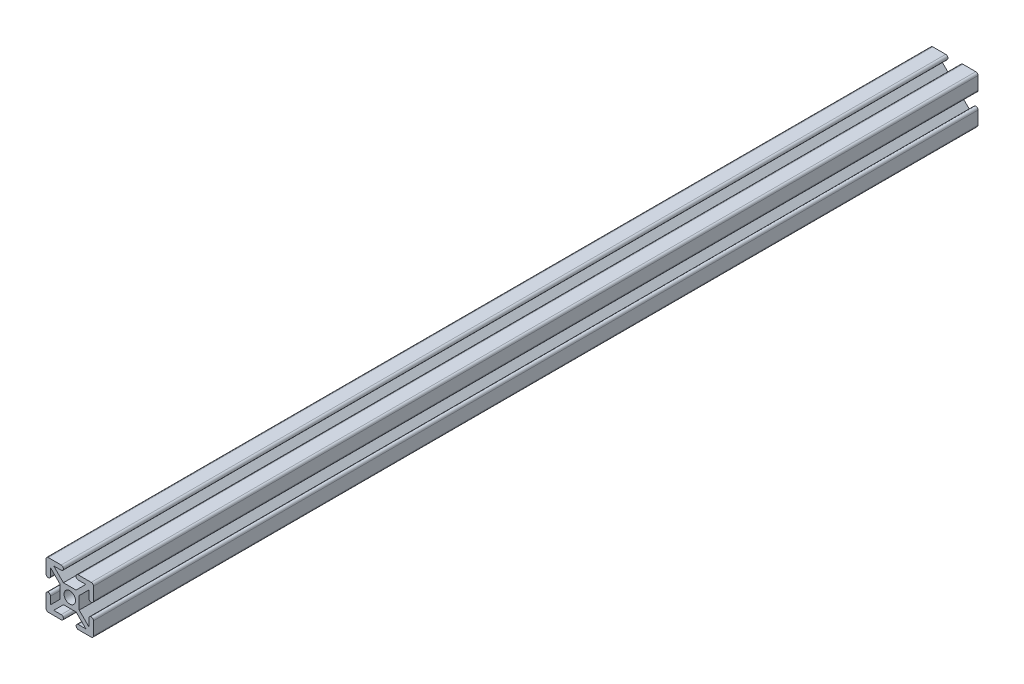
SolidWorks part; units mm, degrees
ref_plane "Alzado" through (0, 0, 0) normal (0, 0, 1) x (1, 0, 0)
ref_plane "Planta" through (0, 0, 0) normal (0, 1, 0) x (1, 0, 0)
ref_plane "Vista lateral" through (0, 0, 0) normal (1, 0, 0) x (0, 0, -1)
sketch "Croquis1" plane through (0, 0, 0) normal (0, 0, 1) x (1, 0, 0)
  line L0 (-21.181, 37.9272) -> (-21.181, 39.3522) construction
  line L1 (-2.1282, 21.7772) -> (2.5968, 21.7772)
  line L2 (-22.606, 47.5021) -> (-22.606, 39.3522)
  line L3 (-21.181, 48.9271) -> (-13.031, 48.9271)
  line L4 (-2.181, 48.9271) -> (5.969, 48.9271)
  line L5 (-17.7032, 21.7772) -> (-12.9782, 21.7772)
  line L6 (-13.606, 37.9272) -> (-13.606, 29.9272)
  line L7 (-22.5532, 28.5022) -> (-22.5532, 20.3522)
  line L8 (-21.1546, 18.9536) -> (-12.9782, 18.9272)
  line L9 (7.394, 47.5021) -> (7.394, 39.4559)
  line L10 (-19.756, 44.0772) -> (-19.756, 39.3522)
  line L11 (7.394, 28.6059) -> (7.394, 20.3522)
  line L12 (-11.606, 47.5021) -> (-13.031, 47.5021) construction
  line L13 (-2.1282, 18.9272) -> (5.969, 18.9272)
  line L14 (-17.756, 46.0771) -> (-13.031, 46.0771)
  line L15 (-19.756, 28.5022) -> (-19.756, 23.7772)
  line L16 (-3.606, 47.5021) -> (-2.181, 47.5021) construction
  line L17 (-2.181, 46.0771) -> (2.544, 46.0771)
  line L18 (5.969, 38.0309) -> (5.969, 39.4559) construction
  line L19 (-11.606, 39.9271) -> (-17.756, 46.0771)
  line L20 (4.544, 44.0771) -> (4.544, 39.4559)
  line L21 (5.969, 30.0309) -> (5.969, 28.6059) construction
  line L22 (-13.606, 37.9272) -> (-19.756, 44.0772)
  line L23 (4.544, 28.6059) -> (4.544, 23.7771)
  line L24 (-3.5532, 20.3522) -> (-2.1282, 20.3522) construction
  line L25 (-13.606, 29.9272) -> (-19.756, 23.7772)
  line L26 (-11.606, 39.9271) -> (-3.606, 39.9271)
  line L27 (-3.606, 39.9271) -> (2.544, 46.0771)
  line L28 (-21.1546, 29.9272) -> (-21.1546, 28.5022) construction
  line L29 (-17.7032, 21.7772) -> (-11.5532, 27.9272)
  line L30 (-11.5532, 27.9272) -> (-3.5532, 27.9272)
  line L31 (-3.5532, 27.9272) -> (2.5968, 21.7772)
  line L32 (-11.5532, 20.3522) -> (-12.9782, 20.3522) construction
  line L33 (-1.606, 29.9271) -> (4.544, 23.7771)
  line L34 (-1.606, 37.9271) -> (4.544, 44.0771)
  line L35 (-1.606, 37.9271) -> (-1.606, 29.9271)
  circle A0 centre (-7.5532, 33.9272) radius 3.645
  arc A1 (-22.606, 39.3522) -> (-19.756, 39.3522) centre (-21.181, 39.3522) ccw
  arc A2 (-13.031, 46.0771) -> (-13.031, 48.9271) centre (-13.031, 47.5021) ccw
  arc A3 (-2.181, 48.9271) -> (-2.181, 46.0771) centre (-2.181, 47.5021) ccw
  arc A4 (4.544, 39.4559) -> (7.394, 39.4559) centre (5.969, 39.4559) ccw
  arc A5 (7.394, 28.6059) -> (4.544, 28.6059) centre (5.969, 28.6059) ccw
  arc A6 (-2.1282, 21.7772) -> (-2.1282, 18.9272) centre (-2.1282, 20.3522) ccw
  arc A7 (-19.756, 28.5022) -> (-22.5532, 28.5022) centre (-21.1546, 28.5022) ccw
  arc A8 (-12.9782, 18.9272) -> (-12.9782, 21.7772) centre (-12.9782, 20.3522) ccw
  arc A9 (-22.5532, 20.3522) -> (-21.1546, 18.9536) centre (-21.1546, 20.3522) ccw
  arc A10 (5.969, 18.9272) -> (7.394, 20.3522) centre (5.969, 20.3522) ccw
  arc A11 (7.394, 47.5021) -> (5.969, 48.9271) centre (5.969, 47.5021) ccw
  arc A12 (-21.181, 48.9271) -> (-22.606, 47.5021) centre (-21.181, 47.5021) ccw
  dimension "D1" = 1.425
  dimension "D2" = 1.425
  dimension "D3" = 1.425
  dimension "D4" = 1.425
  dimension "D5" = 1.425
  dimension "D6" = 1.425
  dimension "D7" = 1.425
extrude "Saliente-Extruir1" add sketch "Croquis1" along normal blind 559.14
